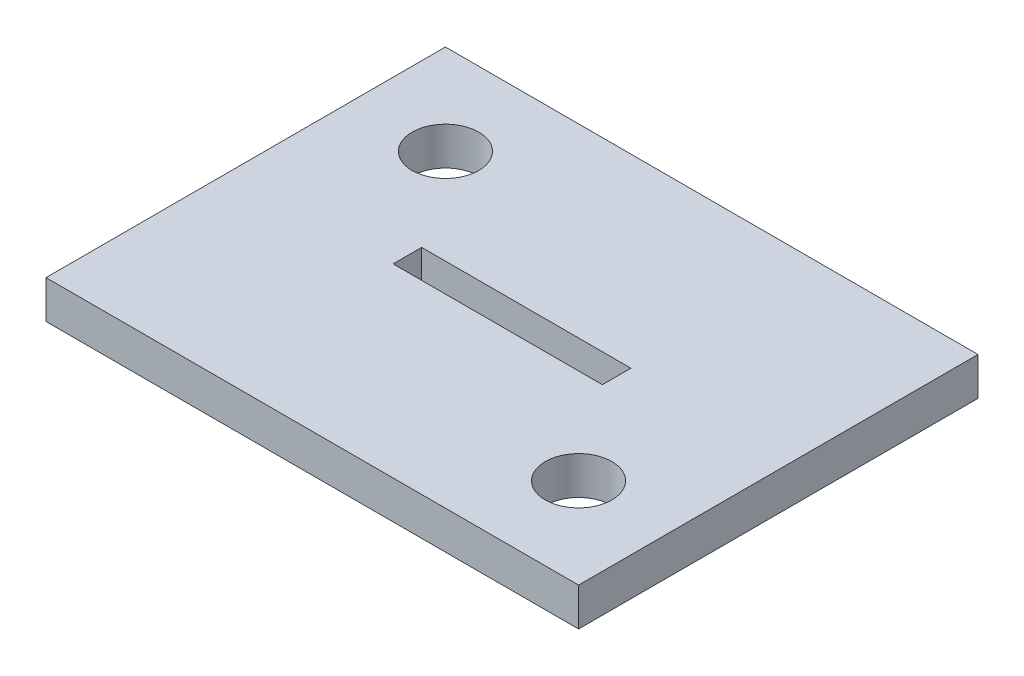
SolidWorks part; units mm, degrees
ref_plane "Piano frontale" through (0, 0, 0) normal (0, 0, 1) x (1, 0, 0)
ref_plane "Piano superiore" through (0, 0, 0) normal (0, 1, 0) x (1, 0, 0)
ref_plane "Piano destro" through (0, 0, 0) normal (1, 0, 0) x (0, 0, -1)
sketch "Schizzo1" plane through (0, 0, 0) normal (0, 1, 0) x (1, 0, 0)
  line L0 (-11.5, 8) -> (-9.25, 5.75) construction
  line L1 (11.5, -8) -> (-11.5, -8) construction
  line L2 (11.5, -8) -> (11.5, 8) construction
  line L3 (11.5, 8) -> (-11.5, 8) construction
  line L4 (-11.5, -8) -> (-11.5, 8) construction
  line L5 (11.5, -8) -> (-11.5, 8) construction
  line L6 (11.5, 8) -> (-11.5, -8) construction
  line L7 (5.5, -0.75) -> (-5.5, -0.75)
  line L8 (5.5, -0.75) -> (5.5, 0.75)
  line L9 (5.5, 0.75) -> (-5.5, 0.75)
  line L10 (-5.5, -0.75) -> (-5.5, 0.75)
  line L11 (5.5, -0.75) -> (-5.5, 0.75) construction
  line L12 (5.5, 0.75) -> (-5.5, -0.75) construction
  line L13 (-9.25, 5.75) -> (9.25, -5.75) construction
  line L14 (9.25, -5.75) -> (11.5, -8) construction
  line L16 (14, -10.5) -> (-14, -10.5)
  line L17 (14, -10.5) -> (14, 10.5)
  line L18 (14, 10.5) -> (-14, 10.5)
  line L19 (-14, -10.5) -> (-14, 10.5)
  line L20 (14, -10.5) -> (-14, 10.5) construction
  line L21 (14, 10.5) -> (-14, -10.5) construction
  circle A0 centre (-9.25, 5.75) radius 1.75
  circle A1 centre (9.25, -5.75) radius 1.75
  point P0 (0, 0)
  point P10 (0, 0)
  point P15 (0, 0)
  dimension "D3" = 3.5
  dimension "D1" = 23
  dimension "D2" = 16
  dimension "D4" = 1.5
  dimension "D5" = 11
  dimension "D6" = 2.25
  dimension "D7" = 2.25
  dimension "D8" = 45
  dimension "D9" = 21
  dimension "D10" = 28
extrude "Estrusione-Estrusione1" add sketch "Schizzo1" along normal blind 2
